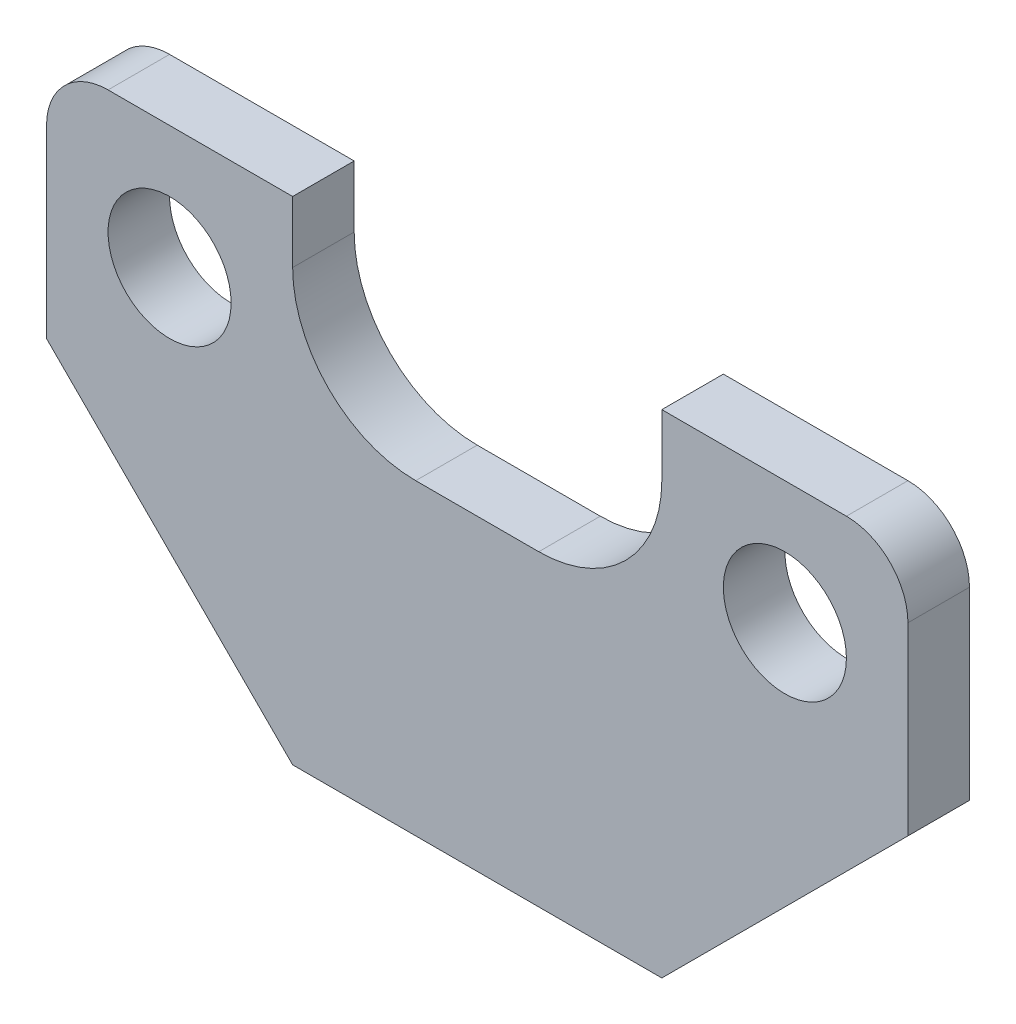
SolidWorks part; units mm, degrees
ref_plane "Ön Düzlem" through (0, 0, 0) normal (0, 0, 1) x (1, 0, 0)
ref_plane "Üst Düzlem" through (0, 0, 0) normal (0, 1, 0) x (1, 0, 0)
ref_plane "Sağ Düzlem" through (0, 0, 0) normal (1, 0, 0) x (0, 0, -1)
sketch "Çizim1" plane through (0, 0, 0) normal (0, 0, 1) x (1, 0, 0)
  line L1 (-28.9976, 16.873) -> (-13.9976, 16.873)
  line L2 (-33.9976, 11.873) -> (-33.9976, -3.127)
  line L3 (-13.9976, -23.127) -> (16.0024, -23.127)
  line L4 (36.0024, 11.873) -> (36.0024, -3.127)
  line L7 (-33.9976, -3.127) -> (-13.9976, -23.127)
  line L8 (16.0024, -23.127) -> (36.0024, -3.127)
  line L9 (16.0024, 16.873) -> (31.0024, 16.873)
  line L11 (-13.9976, 16.873) -> (-13.9976, 11.873)
  line L12 (-3.9976, 1.873) -> (6.0024, 1.873)
  line L13 (16.0024, 16.873) -> (16.0024, 11.873)
  circle A2 centre (-23.9976, 6.873) radius 5
  circle A3 centre (26.0024, 6.873) radius 5
  arc A4 (31.0024, 16.873) -> (36.0024, 11.873) centre (31.0024, 11.873) cw
  arc A5 (-28.9976, 16.873) -> (-33.9976, 11.873) centre (-28.9976, 11.873) ccw
  arc A6 (6.0024, 1.873) -> (16.0024, 11.873) centre (6.0024, 11.873) ccw
  arc A7 (-13.9976, 11.873) -> (-3.9976, 1.873) centre (-3.9976, 11.873) ccw
  point P1 (36.0024, -23.127)
  point P2 (-33.9976, -23.127)
  point P21 (36.0024, 16.873)
  point P24 (-33.9976, 16.873)
  dimension "D3" = 5
  dimension "D7" = 10
  dimension "D8" = 10
  dimension "D10" = 10
  dimension "D13" = 10
  dimension "D15" = 15
  dimension "D14" = 10
  dimension "D1" = 70
  dimension "D2" = 40
  dimension "D4" = 10
  dimension "D9" = 10
  dimension "D11" = 30
  dimension "D12" = 30
extrude "Yükseklik-Ekstrüzyon1" add sketch "Çizim1" along normal blind 5
